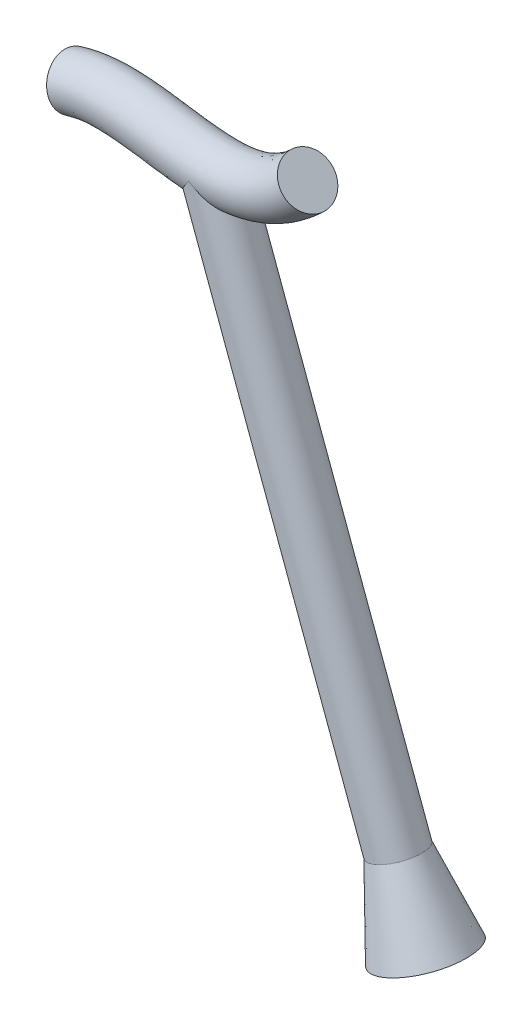
SolidWorks part; units mm, degrees
ref_plane "Alzado" through (0, 0, 0) normal (0, 0, 1) x (1, 0, 0)
ref_plane "Planta" through (0, 0, 0) normal (0, 1, 0) x (1, 0, 0)
ref_plane "Vista lateral" through (0, 0, 0) normal (1, 0, 0) x (0, 0, -1)
sketch "Croquis7" plane through (0, 0, 0) normal (0, 0, 1) x (1, 0, 0)
  spline S0 degree 3 poles (0, 0) (40.0638, 12.9367) (79.9274, -21.1404) (118.2195, 15.69) knots 0 0 0 0 1 1 1 1
  point P2 (0, 0)
  point P4 (0, 0)
  point P10 (0, 0)
  point P11 (0, 0)
  point P13 (0, 0)
  point P14 (76.9903, 1.7546)
  point P15 (86.7122, 6.4773)
  point P16 (88.1236, 3.9086)
  point P17 (118.2195, 15.69)
ref_plane "Plano5" through (0, 0, 0) normal (0.9516, 0.3073, 0) x (0, 0, -1)
sketch "Croquis8" plane through (0, 0, 0) normal (0.9516, 0.3073, 0) x (0, 0, -1)
  circle A0 centre (0, 0) radius 12.5
  dimension "D1" = 25
sweep "Barrer2" add profiles "Croquis8" path "Croquis7"
sketch "Croquis10" plane through (0, 0, 0) normal (0, 0, 1) x (1, 0, 0)
  line L5 (163.6551, -253.2906) -> (70.1464, 0)
  dimension "D1" = 270
ref_plane "Plano6" through (163.6551, -253.2906, 0) normal (-0.3463, 0.9381, 0) x (0.9381, 0.3463, 0)
sketch "Croquis11" plane through (163.6551, -253.2906, 0) normal (-0.3463, 0.9381, 0) x (0.9381, 0.3463, 0)
  circle A0 centre (0, 0) radius 12.5
  dimension "D1" = 25
extrude "Saliente-Extruir1" add sketch "Croquis11" along normal up to next contours A0
sketch "Croquis12" plane through (0, 0, 0) normal (0, 0, 1) x (1, 0, 0)
  line L0 (163.6551, -253.2906) -> (175.3815, -248.9615)
  line L1 (175.3815, -248.9615) -> (198.1468, -283.1959)
  line L2 (198.1468, -283.1959) -> (177.5083, -290.8151)
  line L3 (177.5083, -290.8151) -> (163.6551, -253.2906)
  dimension "D1" = 40
  dimension "D2" = 22
revolve "Revolución3" add sketch "Croquis12" angle 360 about L3
